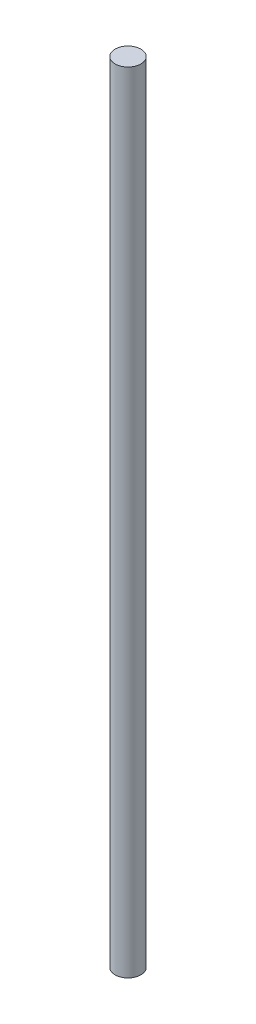
SolidWorks part; units mm, degrees
ref_plane "Front Plane" through (0, 0, 0) normal (0, 0, 1) x (1, 0, 0)
ref_plane "Top Plane" through (0, 0, 0) normal (0, 1, 0) x (1, 0, 0)
ref_plane "Right Plane" through (0, 0, 0) normal (1, 0, 0) x (0, 0, -1)
sketch "Sketch1" plane through (0, 0, 0) normal (0, 1, 0) x (1, 0, 0)
  circle A0 centre (0, 0) radius 4
  dimension "D1" = 8
extrude "Boss-Extrude1" add sketch "Sketch1" along normal blind 245
equation "\"D1@Boss-Extrude1\"=325-80"
